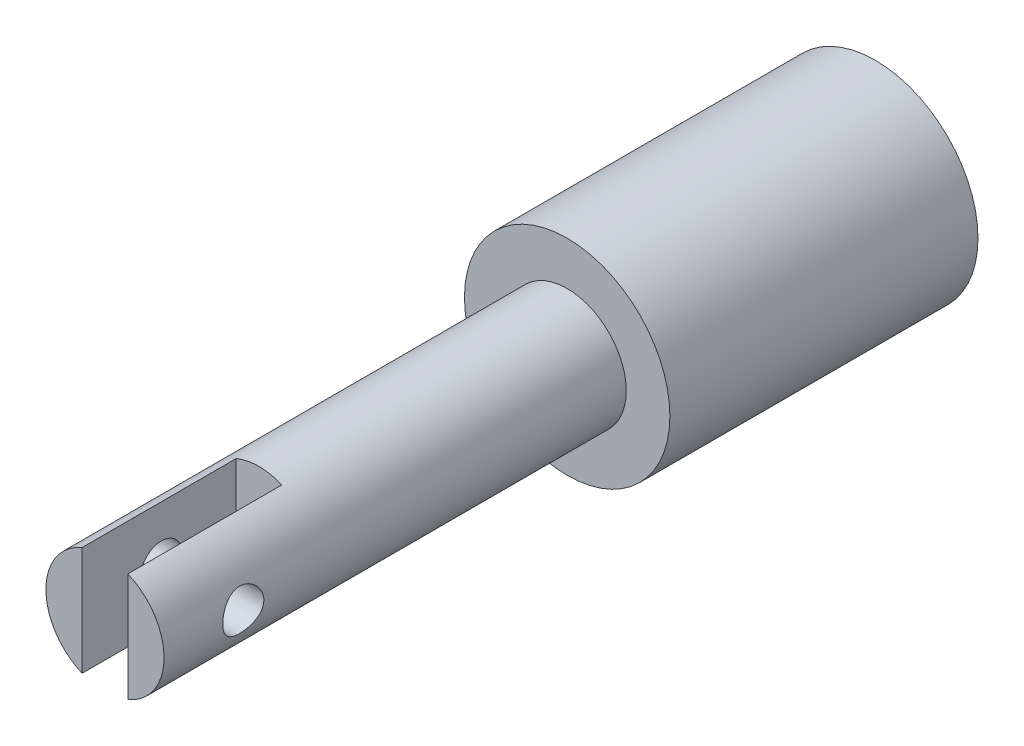
SolidWorks part; units mm, degrees
material "PF"
ref_plane "Plan de face" through (0, 0, 0) normal (0, 0, 1) x (1, 0, 0)
ref_plane "Plan de dessus" through (0, 0, 0) normal (0, 1, 0) x (1, 0, 0)
ref_plane "Plan de droite" through (0, 0, 0) normal (1, 0, 0) x (0, 0, -1)
sketch "Esquisse1" plane through (0, 0, 0) normal (0, 0, 1) x (1, 0, 0)
  circle A0 centre (0, 0) radius 10
extrude "Boss.-Extru.1" add sketch "Esquisse1" along normal blind 30
sketch "Esquisse2" plane through (0, 0, 30) normal (0, 0, 1) x (1, 0, 0)
  circle A0 centre (0, 0) radius 5.7526
extrude "Boss.-Extru.2" add sketch "Esquisse2" along normal blind 30
sketch "Esquisse3" plane through (0, 0, 60) normal (0, 0, 1) x (1, 0, 0)
  line L0 (-2.2252, 5.3048) -> (-2.2252, -5.3048)
  line L1 (0, 9.1269) -> (0, -10.8444) construction
  line L2 (2.2252, 5.3048) -> (2.2252, -5.3048)
  arc A0 (-2.2252, 5.3048) -> (-2.2252, -5.3048) centre (0, 0) ccw
  circle A1 centre (0, 0) radius 5.7526 construction
  arc A2 (2.2252, 5.3048) -> (2.2252, -5.3048) centre (0, 0) cw
extrude "Boss.-Extru.3" add sketch "Esquisse3" along normal blind 15
sketch "Esquisse4" plane through (2.2252, 0, 0) normal (-1, 0, 0) x (0, 0, 1)
  circle A0 centre (67.2844, 0) radius 2
extrude "Enlèv. mat.-Extru.1" cut sketch "Esquisse4" against normal through all and the other way through all
